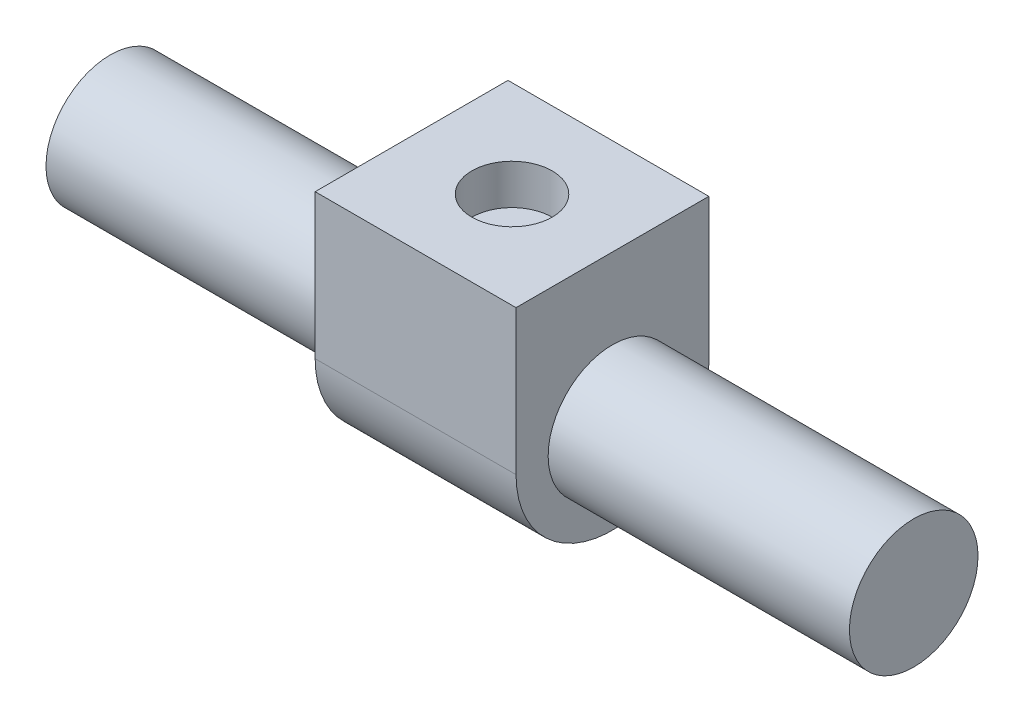
SolidWorks part; units mm, degrees
ref_plane "Front Plane" through (0, 0, 0) normal (0, 0, 1) x (1, 0, 0)
ref_plane "Top Plane" through (0, 0, 0) normal (0, 1, 0) x (1, 0, 0)
ref_plane "Right Plane" through (0, 0, 0) normal (1, 0, 0) x (0, 0, -1)
sketch "Sketch1" plane through (0, 0, 0) normal (1, 0, 0) x (0, 0, -1)
  line L0 (-12, 0) -> (-12, 18)
  line L1 (-12, 18) -> (12, 18)
  line L2 (12, 18) -> (12, 0)
  arc A0 (12, 0) -> (-12, 0) centre (0, 0) cw
  dimension "D2" = 12
  dimension "D1" = 18
extrude "Boss-Extrude1" add sketch "Sketch1" along normal mid plane 25
sketch "Sketch2" plane through (0, 0, 0) normal (1, 0, 0) x (0, 0, -1)
  circle A0 centre (0, 0) radius 8
  dimension "D1" = 16
extrude "Boss-Extrude2" add sketch "Sketch2" along normal mid plane 100
sketch "Sketch3" plane through (0, 18, 0) normal (0, 1, 0) x (1, 0, 0)
  circle A0 centre (0, 0) radius 5
  dimension "D1" = 10
extrude "Cut-Extrude1" cut sketch "Sketch3" against normal blind 5
